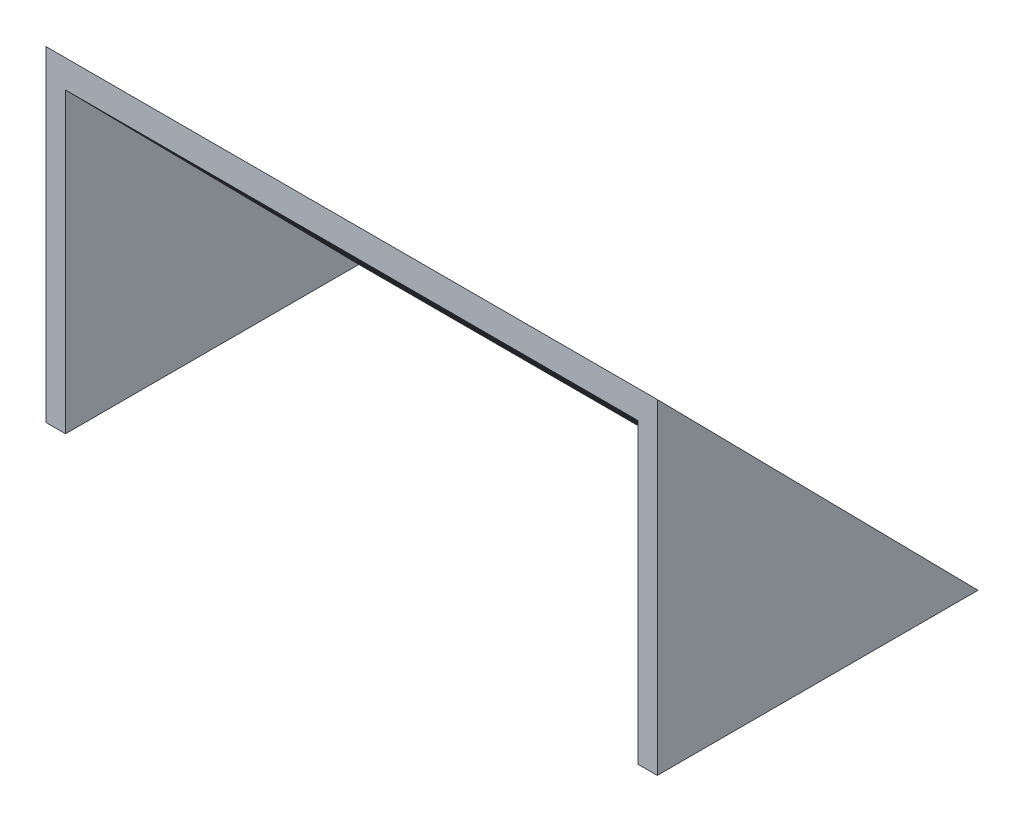
SolidWorks part; units mm, degrees
ref_plane "Přední rovina" through (0, 0, 0) normal (0, 0, 1) x (1, 0, 0)
ref_plane "Horní rovina" through (0, 0, 0) normal (0, 1, 0) x (1, 0, 0)
ref_plane "Pravá rovina" through (0, 0, 0) normal (1, 0, 0) x (0, 0, -1)
sketch "Skica1" plane through (0, 0, 0) normal (1, 0, 0) x (0, 0, -1)
  line L0 (0, 0) -> (0, 20)
  line L1 (0, 20) -> (19.7, 0)
  line L2 (19.7, 0) -> (0, 0)
  dimension "D1" = 19.7
  dimension "20" = 20
extrude "Přidat vysunutím1" add sketch "Skica1" along normal blind 1.2
sketch "Skica2" plane through (0, 9.8489, -9.9989) normal (0, 0.7017, -0.7124) x (-1, 0, 0)
  line L1 (-1.2, 14.2486) -> (-36.35, 14.2486)
  line L2 (-1.2, 14.2486) -> (-1.2, -13.8243)
  line L3 (-1.2, -13.8243) -> (-36.35, -13.8243)
  line L4 (-36.35, 14.2486) -> (-36.35, -13.8243)
  dimension "D1" = 35.15
extrude "Přidat vysunutím2" add sketch "Skica2" against normal blind 1.2
pattern_linear "LinPole1" count 2 spacing 36.35 along (1, 0, 0) of "Přidat vysunutím1"
sketch "Skica3" plane through (37.55, 0, 0) normal (1, 0, 0) x (0, 0, -1)
  line L0 (0, 20) -> (0, 0) construction
  line L1 (0, 16.835) -> (-2.4685, 16.835)
  line L2 (0, 16.835) -> (0, 21.1727)
  line L3 (0, 21.1727) -> (-2.4685, 21.1727)
  line L4 (-2.4685, 16.835) -> (-2.4685, 21.1727)
  line L5 (0, 0) -> (19.7, 0) construction
  line L6 (16.8501, 0) -> (22.214, 0)
  line L7 (16.8501, 0) -> (16.8501, -3.3952)
  line L8 (16.8501, -3.3952) -> (22.214, -3.3952)
  line L9 (22.214, 0) -> (22.214, -3.3952)
  point P12 (16.8501, -3.3952)
extrude "Odebrat vysunutím1" cut sketch "Skica3" against normal through all
